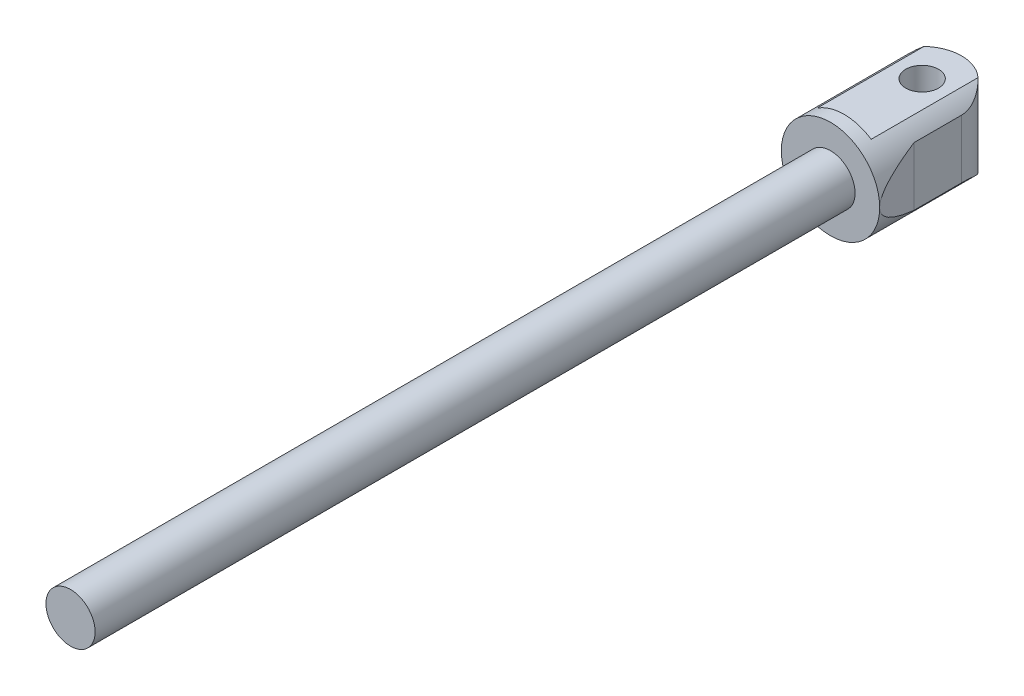
SolidWorks part; units mm, degrees
ref_plane "Front Plane" through (0, 0, 0) normal (0, 0, 1) x (1, 0, 0)
ref_plane "Top Plane" through (0, 0, 0) normal (0, 1, 0) x (1, 0, 0)
ref_plane "Right Plane" through (0, 0, 0) normal (1, 0, 0) x (0, 0, -1)
sketch "Sketch1" plane through (0, 0, 0) normal (0, 0, 1) x (1, 0, 0)
  circle A0 centre (0, 0) radius 37.5
  dimension "D1" = 75
extrude "Boss-Extrude1" add sketch "Sketch1" along normal mid plane 1159
sketch "Sketch2" plane through (0, 0, -579.5) normal (0, 0, -1) x (-1, 0, 0)
  circle A0 centre (0, 0) radius 75
  dimension "D1" = 150
extrude "Boss-Extrude2" add sketch "Sketch2" along normal blind 200
sketch "Sketch3" plane through (0, 0, 0) normal (0, 1, 0) x (1, 0, 0)
  line L0 (75, 779.5) -> (-75, 779.5) construction
  line L1 (0, 579.5) -> (0, 779.5) construction
  line L2 (-37.5, 579.5) -> (37.5, 579.5) construction
  line L3 (75, 579.5) -> (60.24, 646.55)
  line L4 (60.24, 646.55) -> (60.24, 719.26)
  line L5 (-60.24, 646.55) -> (-60.24, 719.26)
  line L6 (-75, 579.5) -> (-60.24, 646.55)
  line L7 (75, 579.5) -> (115.8936, 579.5)
  line L8 (115.8936, 579.5) -> (115.8936, 829.7912)
  line L9 (115.8936, 829.7912) -> (-116.9553, 829.7912)
  line L11 (-116.9553, 829.7912) -> (-116.9553, 579.5)
  line L12 (-116.9553, 579.5) -> (-75, 579.5)
  circle A0 centre (0, 719.26) radius 25
  arc A1 (60.24, 719.26) -> (-60.24, 719.26) centre (0, 719.26) ccw
  point P19 (0, 0)
  dimension "D1" = 50
  dimension "D3" = 60.24
  dimension "D2" = 60.24
  dimension "D4" = 72.71
extrude "Cut-Extrude1" cut sketch "Sketch3" against normal through all both and the other way through all
sketch "Sketch5" plane through (-60.24, 0, 0) normal (-1, 0, 0) x (0, 0, 1)
  line L0 (-579.5, 0) -> (-579.5, 75) construction
  line L1 (-822.5747, 102.4934) -> (-600.36, 102.4934)
  line L2 (-822.5747, 102.4934) -> (-822.5747, 62.67)
  line L3 (-822.5747, 62.67) -> (-600.36, 62.67)
  line L4 (-600.36, 102.4934) -> (-600.36, 62.67)
  line L5 (-579.5, 75) -> (-694.26, 75) construction
  line L6 (0, 0) -> (-994.9468, 0) construction
  line L7 (-822.5747, -62.67) -> (-600.36, -62.67)
  line L8 (-600.36, -102.4934) -> (-600.36, -62.67)
  line L9 (-822.5747, -102.4934) -> (-600.36, -102.4934)
  line L10 (-822.5747, -102.4934) -> (-822.5747, -62.67)
  dimension "D1" = 20.86
  dimension "D2" = 12.33
extrude "Cut-Extrude2" cut sketch "Sketch5" against normal through all both and the other way through all
